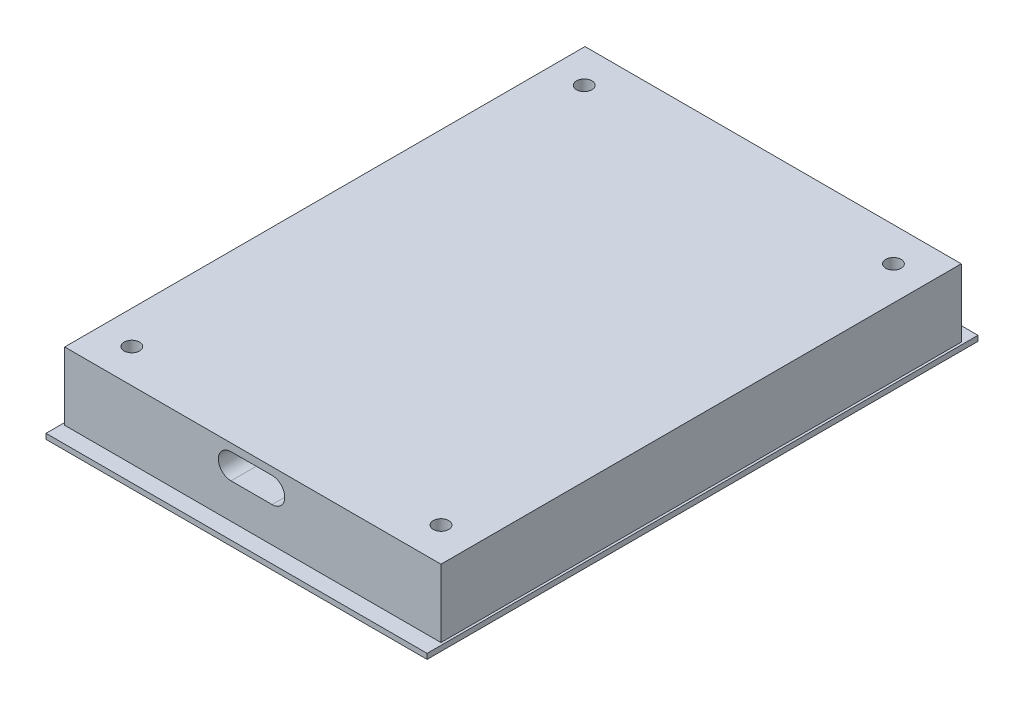
SolidWorks part; units mm, degrees
ref_plane "前视基准面" through (0, 0, 0) normal (0, 0, 1) x (1, 0, 0)
ref_plane "上视基准面" through (0, 0, 0) normal (0, 1, 0) x (1, 0, 0)
ref_plane "右视基准面" through (0, 0, 0) normal (1, 0, 0) x (0, 0, -1)
other "Configuration Table"
sketch "草图1" plane through (0, 0, 0) normal (0, 1, 0) x (1, 0, 0)
  line L1 (-25.27, -36.53) -> (25.27, -36.53)
  line L2 (-25.27, -36.53) -> (-25.27, 36.53)
  line L3 (-25.27, 36.53) -> (25.27, 36.53)
  line L4 (25.27, -36.53) -> (25.27, 36.53)
  line L5 (-25.27, -36.53) -> (25.27, 36.53) construction
  line L6 (-25.27, 36.53) -> (25.27, -36.53) construction
  point P0 (0, 0)
  dimension "D1" = 50.54
  dimension "D2" = 73.06
extrude "凸台-拉伸1" add sketch "草图1" along normal blind 0.7
sketch "草图2" plane through (0, 0.7, 0) normal (0, 1, 0) x (1, 0, 0)
  line L1 (-24.95, 34.63) -> (24.95, 34.63)
  line L3 (-24.95, -34.37) -> (24.95, -34.37)
  line L8 (25.27, 36.53) -> (-25.27, 36.53) construction
  line L9 (24.95, 34.63) -> (24.95, -34.37)
  line L10 (-24.95, 34.63) -> (-24.95, -34.37)
  line L11 (25.27, -36.53) -> (25.27, 36.53) construction
  line L12 (-25.27, 36.53) -> (-25.27, -36.53) construction
  dimension "D1" = 1.9
  dimension "D2" = 0.32
  dimension "D3" = 0.32
extrude "凸台-拉伸2" add sketch "草图2" along normal blind 9
sketch "草图3" plane through (0, 9.7, 0) normal (0, 1, 0) x (1, 0, 0)
  line L5 (24.95, 34.63) -> (-24.95, 34.63) construction
  line L6 (-20.55, 30.13) -> (20.45, 30.13)
  line L7 (-20.55, 30.13) -> (-20.55, -29.87)
  line L8 (-20.55, -29.87) -> (20.45, -29.87)
  line L9 (20.45, 30.13) -> (20.45, -29.87)
  line L10 (24.95, -34.37) -> (24.95, 34.63) construction
  dimension "D1" = 41
  dimension "D2" = 60
  dimension "D3" = 4.5
  dimension "D4" = 4.5
sketch "草图6" plane through (0, 0, 34.37) normal (0, 0, 1) x (1, 0, 0)
  line L0 (-2.895, 7.025) -> (2.555, 7.025) construction
  line L1 (-2.895, 8.7) -> (2.555, 8.7)
  line L2 (-2.895, 5.35) -> (2.555, 5.35)
  line L3 (-24.95, 9.7) -> (24.95, 9.7) construction
  line L5 (-25.27, 0.7) -> (-25.27, 0) construction
  arc A0 (-2.895, 8.7) -> (-2.895, 5.35) centre (-2.895, 7.025) ccw
  arc A1 (2.555, 5.35) -> (2.555, 8.7) centre (2.555, 7.025) ccw
  point P2 (-0.17, 7.025)
  dimension "D1" = 3.35
  dimension "D2" = 5.45
  dimension "D3" = 1
  dimension "D4" = 25.1
extrude "切除-拉伸1" cut sketch "草图6" against normal blind 5
hole_wizard "M2.5 螺纹孔1" positions "草图9" profile "草图8" tap size "M2.5" standard "GB"
sketch "草图9" plane through (0, 9.7, 0) normal (0, 1, 0) x (1, 0, 0)
  point P0 (-20.55, 30.13)
  point P3 (20.45, 30.13)
  point P6 (20.45, -29.87)
  point P9 (-20.55, -29.87)
sketch "草图8" plane through (-20.55, 9.7, -30.13) normal (1, 0, 0) x (0, 0, 1)
  line L0 (0, 0) -> (0, 5.25)
  line L1 (0, 5.25) -> (1.025, 4.6341)
  line L2 (1.025, 4.6341) -> (1.025, 0)
  line L5 (1.025, 0) -> (0, 0)
  line L10 (0, 5.25) -> (-1.025, 4.6341) construction
  line L11 (0, -6.35) -> (0, 107.95) construction
  dimension "螺纹孔钻头直径" = 2.05
  dimension "螺纹孔钻头深度" = 5.25
  dimension "导头角度" = 118
cosmetic thread "孔螺蚊线1" parameters "D1"=3, "D2"=2.5
cosmetic thread "孔螺蚊线2" parameters "D1"=3, "D2"=2.5
cosmetic thread "孔螺蚊线3" parameters "D1"=3, "D2"=2.5
cosmetic thread "孔螺蚊线4" parameters "D1"=3, "D2"=2.5
